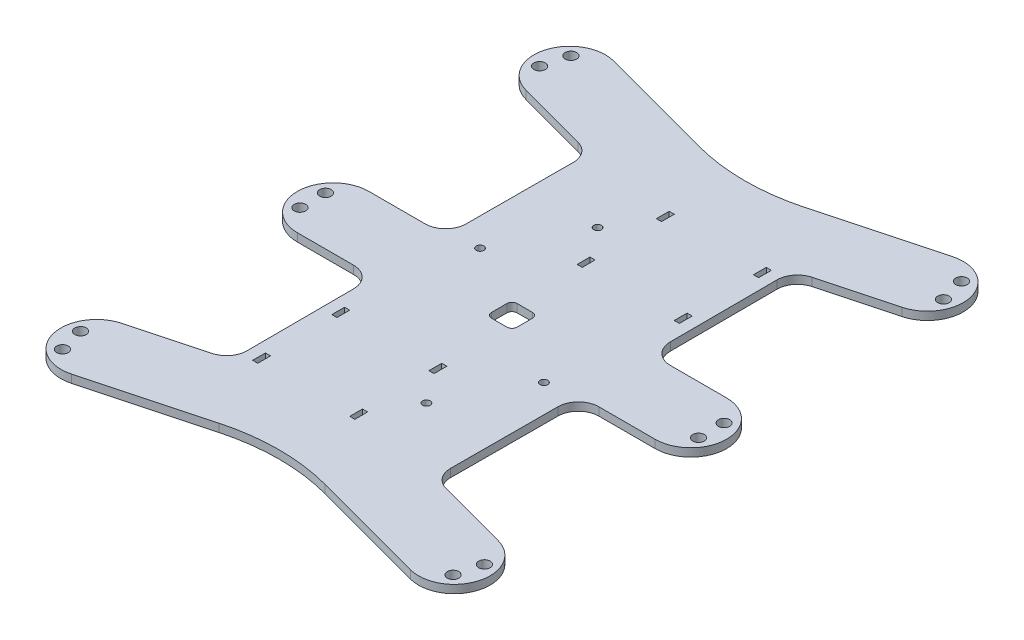
SolidWorks part; units mm, degrees
ref_plane "Front Plane" through (0, 0, 0) normal (0, 0, 1) x (1, 0, 0)
ref_plane "Top Plane" through (0, 0, 0) normal (0, 1, 0) x (1, 0, 0)
ref_plane "Right Plane" through (0, 0, 0) normal (1, 0, 0) x (0, 0, -1)
sketch "Sketch1" plane through (0, 0, 0) normal (0, 1, 0) x (1, 0, 0)
  line L0 (0, 32.1883) -> (0, -21.4181) construction
  line L1 (0, 0) -> (27.1703, 0) construction
  line L2 (-70, 14) -> (-40, 14)
  line L3 (-40, 14) -> (-39.8161, 70)
  line L4 (-39.8161, 70) -> (-73.6235, 79.0587)
  line L5 (-66.3765, 106.1046) -> (0, 88.3191)
  line L10 (-66.3765, 106.1046) -> (-73.6235, 79.0587) construction
  line L12 (-70, 14) -> (-70, -14) construction
  line L14 (-66.3765, -106.1046) -> (0, -88.3191)
  line L15 (-39.8161, -70) -> (-73.6235, -79.0587)
  line L16 (-40, -14) -> (-39.8161, -70)
  line L17 (-70, -14) -> (-40, -14)
  line L18 (66.3765, -106.1046) -> (0, -88.3191)
  line L19 (66.3765, 106.1046) -> (0, 88.3191)
  line L20 (70, 14) -> (70, -14) construction
  line L21 (66.3765, 106.1046) -> (73.6235, 79.0587) construction
  line L22 (70, -14) -> (40, -14)
  line L23 (40, -14) -> (39.8161, -70)
  line L24 (39.8161, -70) -> (73.6235, -79.0587)
  line L25 (39.8161, 70) -> (73.6235, 79.0587)
  line L26 (40, 14) -> (39.8161, 70)
  line L27 (70, 14) -> (40, 14)
  arc A0 (-70, 14) -> (-70, -14) centre (-70, 0) ccw
  arc A1 (-66.3765, 106.1046) -> (-73.6235, 79.0587) centre (-70, 92.5816) ccw
  arc A11 (-66.3765, -106.1046) -> (-73.6235, -79.0587) centre (-70, -92.5816) cw
  arc A18 (66.3765, -106.1046) -> (73.6235, -79.0587) centre (70, -92.5816) ccw
  arc A22 (66.3765, 106.1046) -> (73.6235, 79.0587) centre (70, 92.5816) cw
  arc A23 (70, 14) -> (70, -14) centre (70, 0) cw
  point P118 (-83.523, 96.2051)
  dimension "D2" = 14
  dimension "D3" = 70
  dimension "D1" = 75
  dimension "D5" = 30
  dimension "D6" = 35
  dimension "D7" = 56
extrude "Boss-Extrude1" add sketch "Sketch1" along normal blind 3.175
fillet "Fillet1" radius 80 2 edges at (0, 1.5875, -88.3191) (0, 1.5875, 88.3191)
fillet "Fillet2" radius 8 8 edges at (39.8161, 1.5875, 70) (40, 1.5875, 14) (40, 1.5875, -14) (39.8161, 1.5875, -70) (-39.8161, 1.5875, -70) (-40, 1.5875, -14) (-40, 1.5875, 14) (-39.8161, 1.5875, 70)
sketch "Sketch7" plane through (0, 3.175, 0) normal (0, 1, 0) x (1, 0, 0)
  circle A0 centre (-76.4333, -99.4818) radius 2.25 construction
  circle A1 centre (-79.0215, -89.8226) radius 2.25 construction
  circle A2 centre (-78, -5) radius 2.25 construction
  circle A3 centre (-78, 5) radius 2.25 construction
  circle A4 centre (-79.0215, 89.8226) radius 2.25 construction
  circle A5 centre (-76.4333, 99.4818) radius 2.25 construction
  circle A6 centre (79.0215, 89.8226) radius 2.25 construction
  circle A7 centre (76.4333, 99.4818) radius 2.25 construction
  circle A8 centre (78, -5) radius 2.25 construction
  circle A9 centre (78, 5) radius 2.25 construction
  circle A10 centre (79.0215, -89.8226) radius 2.25 construction
  circle A11 centre (76.4333, -99.4818) radius 2.25 construction
  circle A12 centre (-76.4333, -99.4818) radius 2.25
  circle A13 centre (-79.0215, -89.8226) radius 2.25
  circle A14 centre (-78, -5) radius 2.25
  circle A15 centre (-78, 5) radius 2.25
  circle A16 centre (-79.0215, 89.8226) radius 2.25
  circle A17 centre (-76.4333, 99.4818) radius 2.25
  circle A18 centre (79.0215, 89.8226) radius 2.25
  circle A19 centre (76.4333, 99.4818) radius 2.25
  circle A20 centre (78, -5) radius 2.25
  circle A21 centre (78, 5) radius 2.25
  circle A22 centre (79.0215, -89.8226) radius 2.25
  circle A23 centre (76.4333, -99.4818) radius 2.25
extrude "Cut-Extrude4" cut sketch "Sketch7" against normal blind 10
sketch "Sketch8" plane through (0, 3.175, 0) normal (0, 1, 0) x (1, 0, 0)
  arc A0 (13, -45) -> (13, -48) centre (13, -46.5) ccw construction
  arc A1 (13, -48) -> (13, -45) centre (13, -46.5) ccw construction
  arc A2 (29, -15) -> (29, -18) centre (29, -16.5) ccw construction
  arc A3 (29, -18) -> (29, -15) centre (29, -16.5) ccw construction
  arc A4 (-13, 48) -> (-13, 45) centre (-13, 46.5) ccw construction
  arc A5 (-13, 45) -> (-13, 48) centre (-13, 46.5) ccw construction
  arc A6 (-29, 18) -> (-29, 15) centre (-29, 16.5) ccw construction
  arc A7 (-29, 15) -> (-29, 18) centre (-29, 16.5) ccw construction
  arc A8 (13, -45) -> (13, -48) centre (13, -46.5) ccw
  arc A9 (13, -48) -> (13, -45) centre (13, -46.5) ccw
  arc A10 (29, -15) -> (29, -18) centre (29, -16.5) ccw
  arc A11 (29, -18) -> (29, -15) centre (29, -16.5) ccw
  arc A12 (-13, 48) -> (-13, 45) centre (-13, 46.5) ccw
  arc A13 (-13, 45) -> (-13, 48) centre (-13, 46.5) ccw
  arc A14 (-29, 18) -> (-29, 15) centre (-29, 16.5) ccw
  arc A15 (-29, 15) -> (-29, 18) centre (-29, 16.5) ccw
extrude "Cut-Extrude5" cut sketch "Sketch8" against normal blind 10
sketch "Sketch9" plane through (0, 3.175, 0) normal (0, 1, 0) x (1, 0, 0)
  line L0 (84, 0) -> (-84, 0) construction
  line L1 (0, 91.1411) -> (0, -91.1411) construction
  line L3 (5, 5) -> (-5, 5)
  line L4 (5, 5) -> (5, -5)
  line L5 (5, -5) -> (-5, -5)
  line L6 (-5, 5) -> (-5, -5)
  line L7 (5, 5) -> (-5, -5) construction
  line L8 (5, -5) -> (-5, 5) construction
  arc A0 (70, -14) -> (70, 14) centre (70, 0) ccw construction
  arc A1 (-70, 14) -> (-70, -14) centre (-70, 0) ccw construction
  arc A2 (-20.7055, 93.8671) -> (20.7055, 93.8671) centre (0, 171.1411) ccw construction
  arc A3 (20.7055, -93.8671) -> (-20.7055, -93.8671) centre (0, -171.1411) ccw construction
  point P16 (0, 0)
  dimension "D1" = 10
  dimension "D2" = 10
extrude "Cut-Extrude6" cut sketch "Sketch9" against normal blind 10
fillet "Fillet3" radius 2 4 edges at (5, 1.5875, -5) (-5, 1.5875, -5) (-5, 1.5875, 5) (5, 1.5875, 5)
sketch "Sketch12" plane through (0, 3.175, 0) normal (0, 1, 0) x (1, 0, 0)
  line L1 (-15.5, -92.6571) -> (-15.5, 92.6571) construction
  line L2 (0, 91.1411) -> (0, -91.1411) construction
  line L3 (-84, 0) -> (84, 0) construction
  line L4 (-35.5, -30) -> (-33.5, -30)
  line L5 (-35.5, -30) -> (-35.5, -35)
  line L6 (-35.5, -35) -> (-33.5, -35)
  line L7 (-33.5, -30) -> (-33.5, -35)
  line L8 (-35.5, -61) -> (-33.5, -61)
  line L9 (-35.5, -61) -> (-35.5, -66)
  line L10 (-35.5, -66) -> (-33.5, -66)
  line L11 (-33.5, -61) -> (-33.5, -66)
  line L12 (2.5, -61) -> (2.5, -66)
  line L13 (4.5, -66) -> (2.5, -66)
  line L14 (4.5, -61) -> (4.5, -66)
  line L15 (4.5, -61) -> (2.5, -61)
  line L16 (2.5, -30) -> (2.5, -35)
  line L17 (4.5, -35) -> (2.5, -35)
  line L18 (4.5, -30) -> (4.5, -35)
  line L19 (4.5, -30) -> (2.5, -30)
  line L36 (-2.5, 61) -> (-2.5, 66)
  line L37 (-4.5, 66) -> (-2.5, 66)
  line L38 (-4.5, 61) -> (-4.5, 66)
  line L39 (-4.5, 61) -> (-2.5, 61)
  line L40 (-2.5, 30) -> (-2.5, 35)
  line L41 (-4.5, 35) -> (-2.5, 35)
  line L42 (-4.5, 30) -> (-4.5, 35)
  line L43 (-4.5, 30) -> (-2.5, 30)
  line L44 (35.5, 30) -> (33.5, 30)
  line L45 (35.5, 30) -> (35.5, 35)
  line L46 (35.5, 35) -> (33.5, 35)
  line L47 (33.5, 30) -> (33.5, 35)
  line L48 (35.5, 61) -> (33.5, 61)
  line L49 (35.5, 61) -> (35.5, 66)
  line L50 (35.5, 66) -> (33.5, 66)
  line L51 (33.5, 61) -> (33.5, 66)
  arc A0 (20.7055, -93.8671) -> (-20.7055, -93.8671) centre (0, -171.1411) ccw construction
  arc A1 (-20.7055, 93.8671) -> (20.7055, 93.8671) centre (0, 171.1411) ccw construction
  arc A2 (-70, 14) -> (-70, -14) centre (-70, 0) ccw construction
  arc A3 (70, -14) -> (70, 14) centre (70, 0) ccw construction
  dimension "D1" = 15.5
  dimension "D2" = 26
  dimension "D3" = 2
  dimension "D4" = 5
  dimension "D5" = 18
  dimension "D6" = 30
extrude "Cut-Extrude7" cut sketch "Sketch12" against normal blind 10
